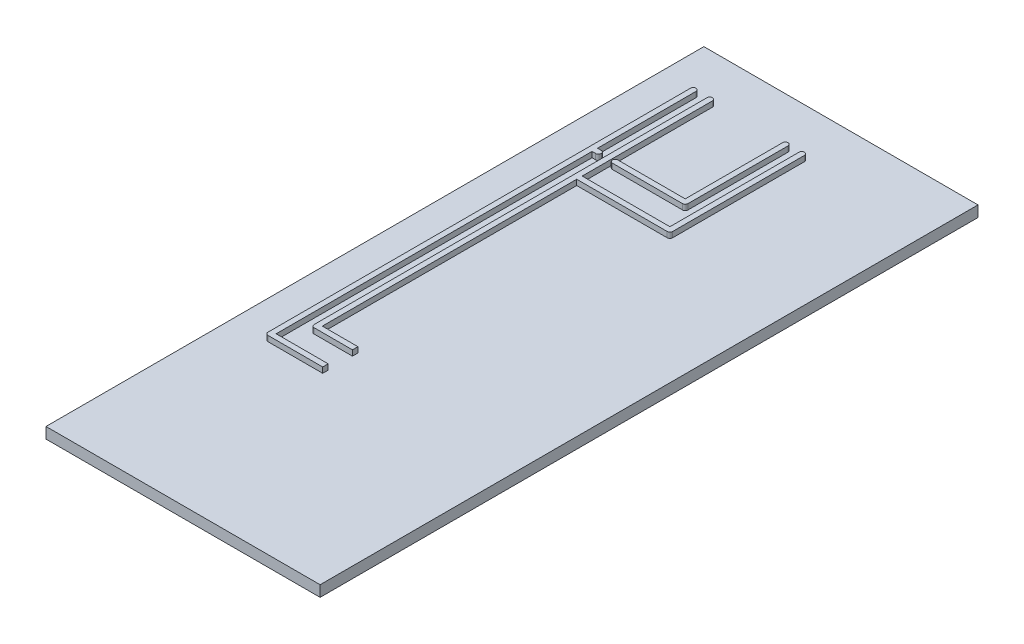
SolidWorks part; units mm, degrees
ref_plane "Front Plane" through (0, 0, 0) normal (0, 0, 1) x (1, 0, 0)
ref_plane "Top Plane" through (0, 0, 0) normal (0, 1, 0) x (1, 0, 0)
ref_plane "Right Plane" through (0, 0, 0) normal (1, 0, 0) x (0, 0, -1)
sketch "Sketch1" plane through (0, 0, 0) normal (0, 1, 0) x (1, 0, 0)
  line L1 (0, 0) -> (50, 0)
  line L2 (0, 0) -> (0, 120)
  line L3 (0, 120) -> (50, 120)
  line L4 (50, 0) -> (50, 120)
extrude "Boss-Extrude1" add sketch "Sketch1" along normal blind 2
sketch "Sketch2" plane through (0, 2, 0) normal (0, 1, 0) x (1, 0, 0)
  line L0 (0, 0) -> (16.8451, 0)
  line L1 (0, 0) -> (50, 0) construction
  line L2 (25, 87.4555) -> (25, 120)
  line L3 (16.8451, 0) -> (33.1549, 0)
  line L4 (16.8451, 0) -> (16.8451, 44.5751)
  line L5 (16.8451, 44.5751) -> (33.1549, 44.5751)
  line L6 (33.1549, 0) -> (33.1549, 44.5751)
  line L8 (9.85, 87.4555) -> (9.85, 92.7509)
  line L9 (9.85, 87.4555) -> (9.85, 92.7509) construction
  line L10 (7.35, 92.2509) -> (7.35, 34.6308)
  line L11 (25, 44.5751) -> (25, 86.4555)
  line L12 (50, 120) -> (0, 120) construction
  line L14 (8.5193, 92.7509) -> (23.35, 92.7509)
  line L15 (26.85, 87.4555) -> (26.85, 111.0052)
  line L16 (26.85, 111.0052) -> (26.35, 111.0052)
  line L17 (23.85, 111.0052) -> (23.85, 93.2509)
  line L19 (16.8451, 39.0516) -> (9.85, 39.0516)
  line L20 (16.8451, 40.0516) -> (10.35, 40.0516)
  line L22 (9.35, 39.5516) -> (9.35, 111.2153)
  line L23 (10.35, 39.5516) -> (10.35, 111.2153)
  line L28 (7.35, 111.2153) -> (7.35, 93.2509)
  line L29 (6.35, 111.2153) -> (6.35, 34.1308)
  line L31 (7.35, 34.6308) -> (16.8451, 34.6308)
  line L32 (6.85, 33.6308) -> (16.8451, 33.6308)
  line L34 (9.85, 87.4555) -> (26.85, 87.4555)
  line L35 (9.85, 86.4555) -> (26.85, 86.4555)
  line L36 (26.85, 87.4555) -> (26.85, 111.0052) construction
  line L37 (26.35, 86.9555) -> (26.35, 111.0052)
  line L38 (27.35, 86.9555) -> (27.35, 111.0052)
  line L39 (23.85, 111.0052) -> (23.85, 93.2509) construction
  line L40 (24.35, 111.0052) -> (24.35, 92.7509)
  line L41 (23.35, 111.0052) -> (23.35, 92.7509)
  line L42 (23.35, 92.7509) -> (11.0556, 92.7509) construction
  line L43 (23.85, 92.2509) -> (11.0556, 92.2509)
  line L44 (23.85, 93.2509) -> (11.0556, 93.2509)
  line L46 (7.35, 93.2509) -> (8.0193, 93.2509)
  line L47 (7.35, 92.2509) -> (8.0193, 92.2509)
  line L51 (24.35, 111.0052) -> (23.85, 111.0052)
  line L52 (25, 44.5751) -> (25, 0)
  arc A0 (16.8451, 39.0516) -> (16.8451, 40.0516) centre (16.8451, 39.5516) ccw
  arc A1 (9.35, 39.5516) -> (9.85, 39.0516) centre (9.85, 39.5516) ccw
  arc A2 (9.35, 39.5516) -> (10.35, 39.5516) centre (9.85, 39.5516) ccw
  arc A3 (10.35, 111.2153) -> (9.35, 111.2153) centre (9.85, 111.2153) ccw
  arc A4 (10.35, 111.2153) -> (9.85, 111.7153) centre (9.85, 111.2153) ccw
  arc A5 (6.85, 111.7153) -> (6.35, 111.2153) centre (6.85, 111.2153) ccw
  arc A6 (7.35, 111.2153) -> (6.35, 111.2153) centre (6.85, 111.2153) ccw
  arc A7 (6.35, 34.1308) -> (6.85, 33.6308) centre (6.85, 34.1308) ccw
  arc A8 (6.35, 34.1308) -> (6.85, 33.6308) centre (6.85, 34.1308) ccw
  arc A9 (16.8451, 33.6308) -> (16.8451, 34.6308) centre (16.8451, 34.1308) ccw
  arc A10 (9.85, 87.4555) -> (9.85, 86.4555) centre (9.85, 86.9555) ccw
  arc A11 (26.85, 86.4555) -> (26.85, 87.4555) centre (26.85, 86.9555) ccw
  arc A12 (26.35, 86.9555) -> (27.35, 86.9555) centre (26.85, 86.9555) ccw
  arc A13 (27.35, 111.0052) -> (26.35, 111.0052) centre (26.85, 111.0052) ccw
  arc A14 (24.35, 111.0052) -> (23.35, 111.0052) centre (23.85, 111.0052) ccw
  arc A15 (23.35, 92.7509) -> (24.35, 92.7509) centre (23.85, 92.7509) ccw
  arc A16 (23.85, 92.2509) -> (23.85, 93.2509) centre (23.85, 92.7509) ccw
  arc A17 (11.0556, 93.2509) -> (11.0556, 92.2509) centre (11.0556, 92.7509) ccw
  arc A19 (8.0193, 92.2509) -> (8.0193, 93.2509) centre (8.0193, 92.7509) ccw
  point P22 (13.3475, 39.5516)
  point P30 (9.85, 75.3834)
  point P36 (8.35, 111.2153)
  point P42 (6.85, 72.673)
  point P48 (11.8475, 34.1308)
  point P53 (18.35, 86.9555)
  point P59 (26.85, 98.9803)
  point P64 (23.85, 101.878)
  point P71 (17.4528, 92.7509)
  point P76 (7.4346, 92.7509)
extrude "Boss-Extrude3" add sketch "Sketch2" along normal blind 1 contours A2 L19 L4 L20 L23 | A10 L22 A1 A2 L23 L35 | L47 A19 L46 L28 A6 A5 L29 A7 L32 L4 L31 L10 | L23 A3 L22 L14 | L8 L34 L23 L14 | A10 L8 L14 L22 | L44 A17 L14 L41 | L14 A17 L43 A15 | A12 L37 L34 L23 L35 | L37 A12 A11 L34 | L38 A13 L16 L15 A11 | L37 L34 L15 L16 | A16 L40 L51 L17 | A15 A16 L44 L41 | L51 A14 L41 L44 L17 | L34 A10 L35 L23
